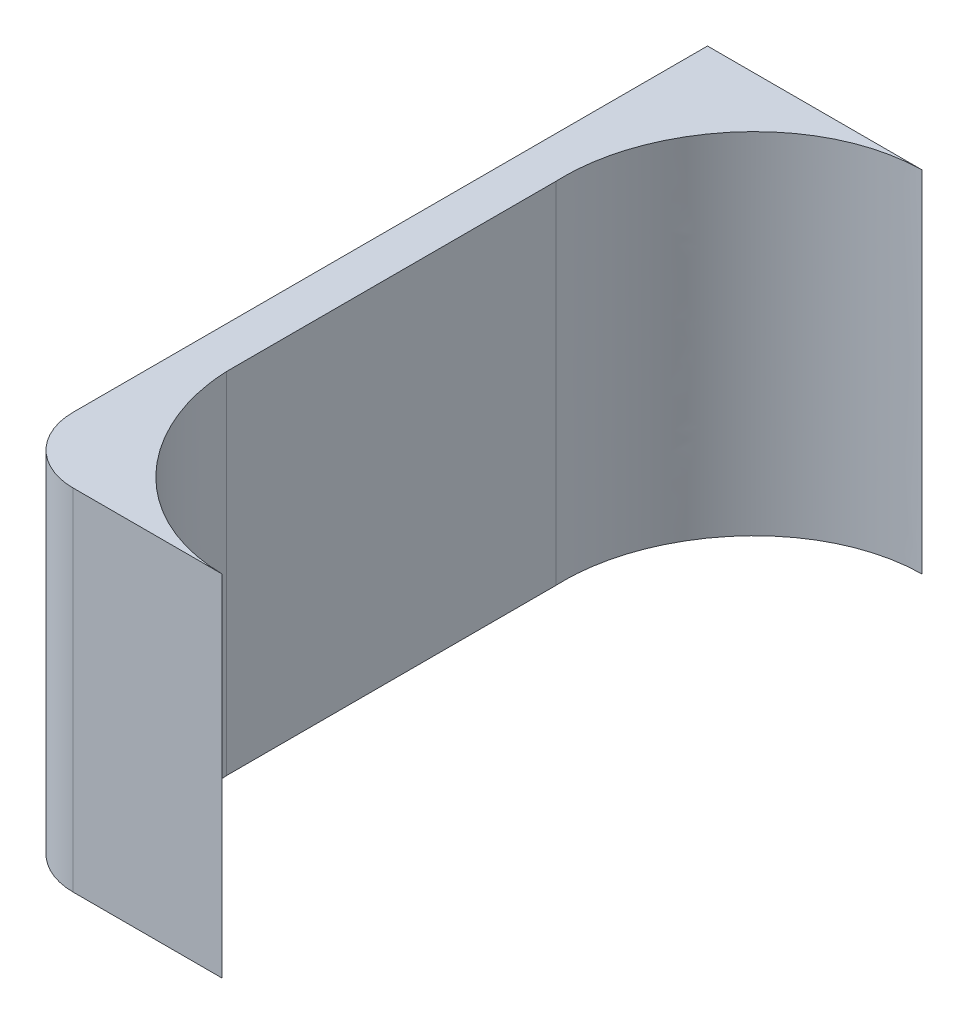
SolidWorks part; units mm, degrees
material "PE High Density"
ref_plane "Front Plane" through (0, 0, 0) normal (0, 0, 1) x (1, 0, 0)
ref_plane "Top Plane" through (0, 0, 0) normal (0, 1, 0) x (1, 0, 0)
ref_plane "Right Plane" through (0, 0, 0) normal (1, 0, 0) x (0, 0, -1)
sketch "Sketch1" plane through (0, 0, 0) normal (0, 0, 1) x (1, 0, 0)
  line L1 (-30, 40) -> (30, 40)
  line L2 (-30, 40) -> (-30, -40)
  line L3 (-30, -40) -> (30, -40)
  line L4 (30, 40) -> (30, -40)
  line L5 (-30, 40) -> (30, -40) construction
  line L6 (-30, -40) -> (30, 40) construction
  point P0 (0, 0)
  dimension "D1" = 80
  dimension "D2" = 60
extrude "Boss-Extrude1" add sketch "Sketch1" along normal blind 160
sketch "Sketch2" plane through (0, 40, 0) normal (0, 1, 0) x (1, 0, 0)
  line L0 (-20.5384, -44.0538) -> (-20.5384, -119.4659)
  line L2 (-30, -80) -> (30, -80) construction
  line L3 (-30, -160) -> (-30, 0) construction
  line L4 (30, 0) -> (-30, 0) construction
  line L6 (19, 0) -> (30, 0)
  line L7 (30, 0) -> (30, -160)
  line L9 (19, -160) -> (30, -160)
  spline S0 degree 3 poles (19, -160) (-4.3707, -159.5938) (-21.4956, -137.8826) (-20.5384, -115.9462) knots 0 0 0 0 1 1 1 1
  spline S1 degree 3 poles (19, 0) (-4.3707, -0.4062) (-21.4956, -22.1174) (-20.5384, -44.0538) knots 0 0 0 0 1 1 1 1
  line M5 (30, 0) -> (-30, 0)
  line M7 (-30, -160) -> (30, -160)
  line M8 (30, -160) -> (30, 0)
  dimension "D1" = 11
  dimension "D2" = 27.8413
  dimension "D6" = 65.7544
  dimension "D7" = 4.2698
  dimension "D3" = 65.7544
  dimension "D8" = 9.5443
  dimension "D9" = 25.7243
extrude "Cut-Extrude1" cut sketch "Sketch2" against normal through all contours L0 L2 L7 S1 M5 | L2 L0 S0 M7 M8
fillet "Fillet1" radius 15 1 edges at (-30, 0, 160)
